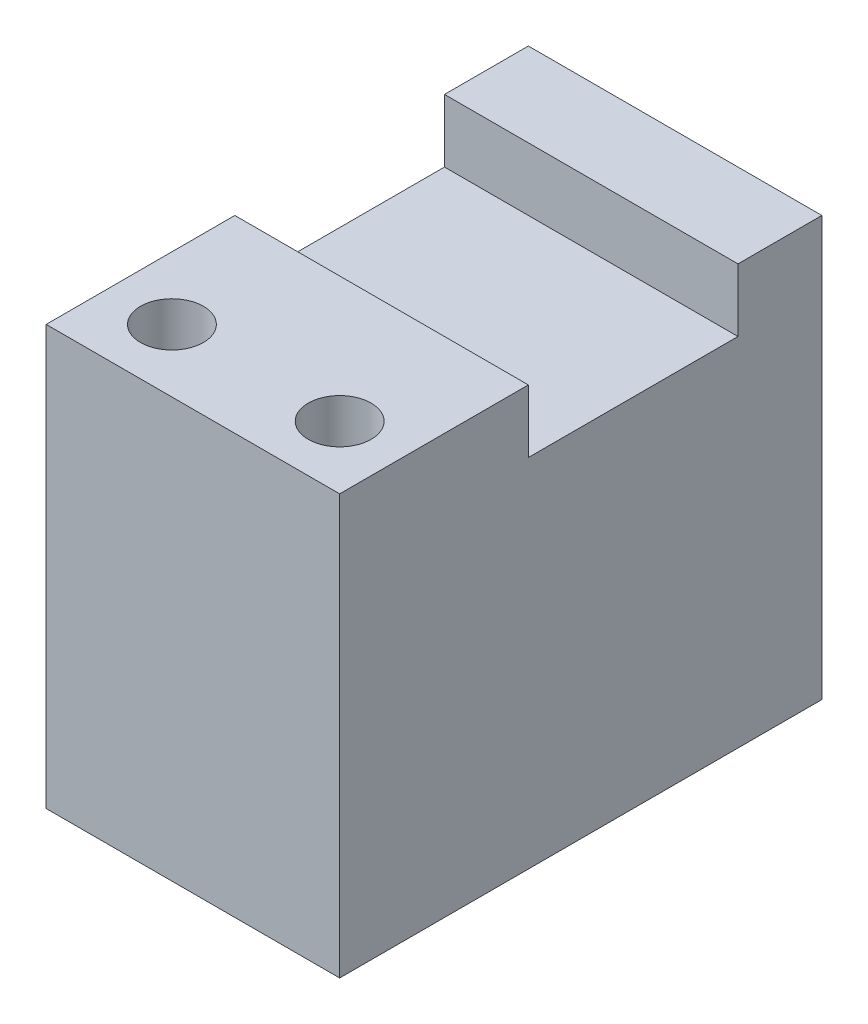
SolidWorks part; units mm, degrees
material "MC nylon"
ref_plane "Front Plane" through (0, 0, 0) normal (0, 0, 1) x (1, 0, 0)
ref_plane "Top Plane" through (0, 0, 0) normal (0, 1, 0) x (1, 0, 0)
ref_plane "Right Plane" through (0, 0, 0) normal (1, 0, 0) x (0, 0, -1)
sketch "Sketch1" plane through (0, 0, 0) normal (0, 1, 0) x (1, 0, 0)
  line L1 (0, 0) -> (14, 0)
  line L2 (0, 0) -> (0, 23)
  line L3 (0, 23) -> (14, 23)
  line L4 (14, 0) -> (14, 23)
  dimension "D1" = 14
  dimension "D2" = 23
extrude "Boss-Extrude1" add sketch "Sketch1" against normal blind 20
sketch "Sketch2" plane through (0, 0, 0) normal (0, 1, 0) x (1, 0, 0)
  line L0 (14, 0) -> (14, 23) construction
  line L3 (0, 19) -> (14, 19)
  line L5 (0, 9) -> (14, 9)
  line L10 (0, 19) -> (0, 9)
  line L14 (14, 23) -> (0, 23) construction
  line L15 (0, 23) -> (0, 0) construction
  line L21 (0, 19) -> (0, 9)
  line L23 (14, 19) -> (14, 0)
  dimension "D1" = 10
  dimension "D2" = 4
extrude "Cut-Extrude1" cut sketch "Sketch2" against normal blind 3
hole_wizard "Ø3.0 (3) Diameter Hole1" positions "Sketch6" profile "Sketch7" hole size "Ø3.0" standard "JIS"
sketch "Sketch6" plane through (0, 0, 0) normal (0, 1, 0) x (1, 0, 0)
  line L0 (14, 0) -> (14, 9) construction
  line L1 (0, 0) -> (14, 0) construction
  point P0 (11, 3)
  point P2 (3, 3)
  dimension "D1" = 3
  dimension "D2" = 3
  dimension "D3" = 8
sketch "Sketch7" plane through (11, 0, -3) normal (1, 0, 0) x (0, 0, 1)
  line L0 (0, 0) -> (0, 5.9013)
  line L1 (0, 5.9013) -> (1.5, 5)
  line L2 (1.5, 5) -> (1.5, 0)
  line L5 (1.5, 0) -> (0, 0)
  line L10 (0, 5.9013) -> (-1.5, 5) construction
  line L11 (0, -6.35) -> (0, 107.95) construction
  dimension "Hole Dia." = 3
  dimension "Hole Depth" = 5
  dimension "Drill Angle" = 118
hole_wizard "M10x1.0 Tapped Hole1" positions "Sketch8" profile "Sketch9" tap size "M10x1.0" standard "JIS"
sketch "Sketch8" plane through (0, -20, 0) normal (0, -1, 0) x (-1, 0, 0)
  line L0 (-14, 0) -> (-14, 23) construction
  line L1 (-14, 23) -> (0, 23) construction
  point P0 (-7, 15)
  dimension "D1" = 7
  dimension "D2" = 8
sketch "Sketch9" plane through (7, -20, -15) normal (1, 0, 0) x (0, 0, -1)
  line L0 (0, 0) -> (0, 14.7039)
  line L1 (0, 14.7039) -> (4.5, 12)
  line L2 (4.5, 12) -> (4.5, 0)
  line L5 (4.5, 0) -> (0, 0)
  line L10 (0, 14.7039) -> (-4.5, 12) construction
  line L11 (0, -6.35) -> (0, 107.95) construction
  dimension "Tap Drill Dia." = 9
  dimension "Tap Drill Depth" = 12
  dimension "Drill Angle" = 118
cosmetic thread "Hole Thread1" parameters "D1"=12, "D2"=10
